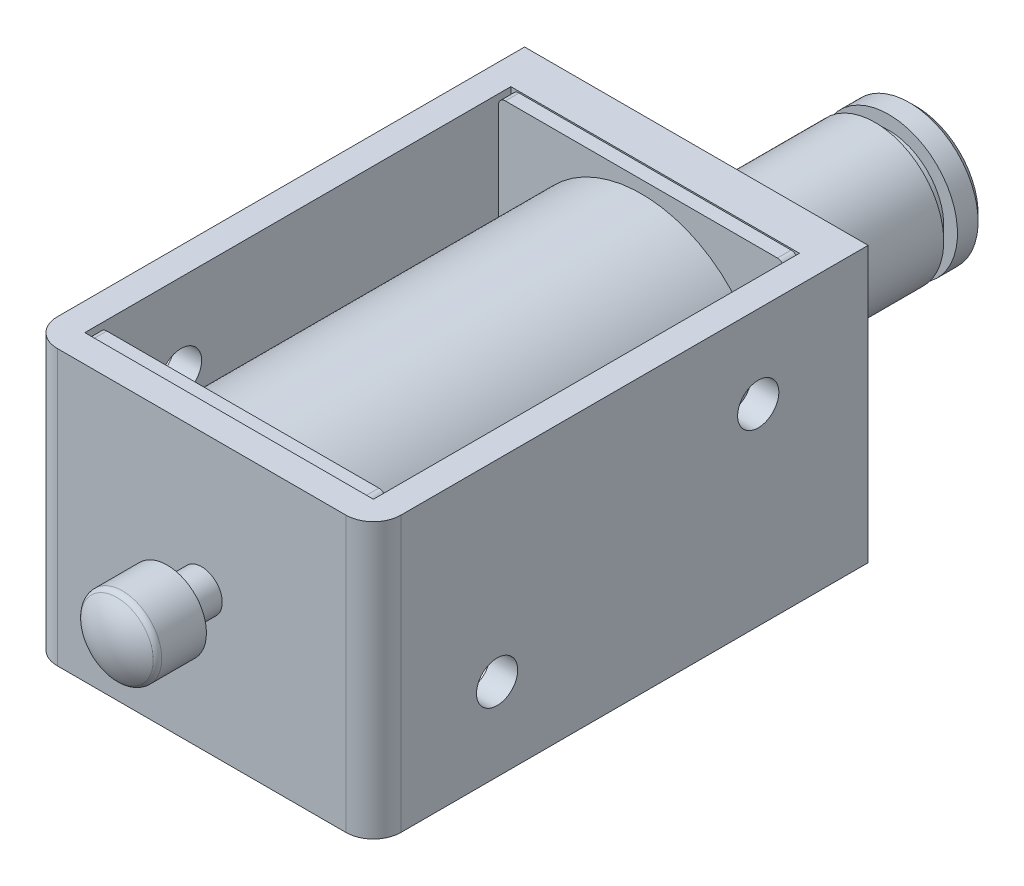
SolidWorks part; units mm, degrees
ref_plane "正面" through (0, 0, 0) normal (0, 0, 1) x (1, 0, 0)
ref_plane "平面" through (0, 0, 0) normal (0, 1, 0) x (1, 0, 0)
ref_plane "右側面" through (0, 0, 0) normal (1, 0, 0) x (0, 0, -1)
sketch "ｽｹｯﾁ1" plane through (0, 0, 0) normal (0, 1, 0) x (1, 0, 0)
  line L0 (2, 17.5) -> (0, 17.5) construction
  line L1 (2, 0) -> (23, 0)
  line L2 (0, 2) -> (0, 36)
  line L3 (0, 36) -> (25, 36)
  line L4 (25, 2) -> (25, 36)
  line L5 (2, 33) -> (23, 33)
  line L6 (2, 33) -> (2, 2)
  line L7 (2, 2) -> (23, 2)
  line L8 (23, 33) -> (23, 2)
  line L9 (23, 17.5) -> (25, 17.5) construction
  line L10 (12.5, 2) -> (12.5, 0) construction
  line L11 (12.5, 33) -> (12.5, 36) construction
  arc A0 (2, 0) -> (0, 2) centre (2, 2) cw
  arc A1 (23, 0) -> (25, 2) centre (23, 2) ccw
  point P19 (0, 0)
  point P22 (25, 0)
  dimension "D5" = 2
  dimension "D1" = 25
  dimension "D2" = 36
  dimension "D3" = 2
  dimension "D4" = 3
extrude "ﾎﾞｽ - 押し出し1" add sketch "ｽｹｯﾁ1" along normal blind 20
sketch "ｽｹｯﾁ14" plane through (25, 0, 0) normal (1, 0, 0) x (0, 0, -1)
  line L0 (0, 6) -> (36, 6) construction
  line L1 (0, 20) -> (0, 0) construction
  line L2 (36, 20) -> (36, 0) construction
  line L3 (36, 14) -> (0, 14) construction
  line L4 (9, 0) -> (9, 20) construction
  line L5 (2, 0) -> (36, 0) construction
  line L6 (2, 20) -> (36, 20) construction
  line L7 (28, 20) -> (28, 0) construction
  circle A0 centre (9, 6) radius 1.5
  circle A1 centre (28, 14) radius 1.5
  point P20 (0, 0)
  dimension "D1" = 3
  dimension "D2" = 6
  dimension "D3" = 9
  dimension "D4" = 6
  dimension "D5" = 8
extrude "ｶｯﾄ - 押し出し5" cut sketch "ｽｹｯﾁ14" against normal up to next
sketch "ｽｹｯﾁ15" plane through (0, 0, 0) normal (-1, 0, 0) x (0, 0, 1)
  line L0 (-36, 6) -> (0, 6) construction
  line L1 (-36, 20) -> (-36, 0) construction
  line L2 (0, 20) -> (0, 0) construction
  line L3 (-36, 14) -> (0, 14) construction
  line L4 (-28, 0) -> (-28, 20) construction
  line L5 (-36, 0) -> (-2, 0) construction
  line L6 (-36, 20) -> (-2, 20) construction
  line L7 (-9, 20) -> (-9, 0) construction
  circle A0 centre (-28, 6) radius 1.5
  circle A1 centre (-9, 14) radius 1.5
  dimension "D5" = 3
  dimension "D1" = 8
  dimension "D2" = 6
  dimension "D3" = 9
  dimension "D4" = 6
extrude "ｶｯﾄ - 押し出し6" cut sketch "ｽｹｯﾁ15" against normal up to next
sketch "ｽｹｯﾁ2" plane through (0, 0, -2) normal (0, 0, -1) x (-1, 0, 0)
  line L18 (-22.9, 0.1) -> (-2.1, 0.1)
  line L19 (-2.1, 0.1) -> (-2.1, 19.9)
  line L20 (-22.9, 19.9) -> (-22.9, 0.1)
  line L21 (-2.1, 19.9) -> (-22.9, 19.9)
  line L22 (-22.4, 0.1) -> (-2.6, 0.1)
  line L23 (-2.1, 0.6) -> (-2.1, 19.4)
  line L24 (-22.9, 19.4) -> (-22.9, 0.6)
  line L25 (-2.6, 19.9) -> (-22.4, 19.9)
  arc A4 (-22.4, 0.1) -> (-22.9, 0.6) centre (-22.4, 0.6) cw
  arc A5 (-2.6, 0.1) -> (-2.1, 0.6) centre (-2.6, 0.6) ccw
  arc A6 (-2.1, 19.4) -> (-2.6, 19.9) centre (-2.6, 19.4) ccw
  arc A7 (-22.9, 19.4) -> (-22.4, 19.9) centre (-22.4, 19.4) cw
  dimension "D1" = 0.1
  dimension "D2" = 0.5
extrude "ﾎﾞｽ - 押し出し2" add sketch "ｽｹｯﾁ2" along normal blind 1
sketch "ｽｹｯﾁ3" plane through (0, 0, -33) normal (0, 0, 1) x (1, 0, 0)
  line L8 (2.1, 0.1) -> (22.9, 0.1)
  line L9 (22.9, 0.1) -> (22.9, 19.9)
  line L10 (22.9, 19.9) -> (2.1, 19.9)
  line L11 (2.1, 19.9) -> (2.1, 0.1)
  line L12 (2.6, 0.1) -> (22.4, 0.1)
  line L13 (22.9, 0.6) -> (22.9, 19.4)
  line L14 (22.4, 19.9) -> (2.6, 19.9)
  line L15 (2.1, 19.4) -> (2.1, 0.6)
  arc A0 (2.6, 0.1) -> (2.1, 0.6) centre (2.6, 0.6) cw
  arc A1 (22.4, 0.1) -> (22.9, 0.6) centre (22.4, 0.6) ccw
  arc A2 (22.9, 19.4) -> (22.4, 19.9) centre (22.4, 19.4) ccw
  arc A3 (2.6, 19.9) -> (2.1, 19.4) centre (2.6, 19.4) ccw
  dimension "D2" = 0.5
  dimension "D1" = 0.1
extrude "ﾎﾞｽ - 押し出し3" add sketch "ｽｹｯﾁ3" along normal blind 1
sketch "ｽｹｯﾁ4" plane through (0, 0, 0) normal (0, 0, 1) x (1, 0, 0)
  line L0 (12.5, 20) -> (12.5, 0) construction
  line L1 (2, 20) -> (23, 20) construction
  line L2 (2, 0) -> (23, 0) construction
  line L3 (0, 10) -> (25, 10) construction
  line L4 (0, 20) -> (0, 0) construction
  line L5 (25, 20) -> (25, 0) construction
  circle A0 centre (12.5, 10) radius 1.5
  dimension "D1" = 3
extrude "ｶｯﾄ - 押し出し1" cut sketch "ｽｹｯﾁ4" against normal up to surface (3 mm away) up to face at (12.5, 10, -3)
sketch "ｽｹｯﾁ5" plane through (0, 0, -36) normal (0, 0, -1) x (-1, 0, 0)
  line L0 (-12.5, 20) -> (-12.5, 0) construction
  line L1 (-25, 20) -> (0, 20) construction
  line L2 (-25, 0) -> (0, 0) construction
  line L3 (-25, 10) -> (0, 10) construction
  line L4 (-25, 20) -> (-25, 0) construction
  line L5 (0, 20) -> (0, 0) construction
  circle A0 centre (-12.5, 10) radius 5
  dimension "D1" = 10
extrude "ｶｯﾄ - 押し出し2" cut sketch "ｽｹｯﾁ5" against normal up to surface (4 mm away) up to face at (12.5, 10, -32)
ref_plane "平面1" through (0, 10, 0) normal (0, 1, 0) x (1, 0, 0)
sketch "ｽｹｯﾁ6" plane through (0, 10, 0) normal (0, 1, 0) x (1, 0, 0)
  line L0 (12.5, 32) -> (12.5, 3)
  line L1 (22.4, 32) -> (2.6, 32) construction
  line L2 (2.6, 3) -> (22.4, 3) construction
  line L3 (12.5, 3) -> (3.5, 3)
  line L4 (3.5, 3) -> (3.5, 32)
  line L5 (3.5, 32) -> (12.5, 32)
  line L6 (2, 33) -> (2, 2) construction
  dimension "D1" = 1.5
revolve "回転1" add sketch "ｽｹｯﾁ6" angle 360 about L0
sketch "ｽｹｯﾁ7" plane through (0, 0, -3) normal (0, 0, -1) x (-1, 0, 0)
  circle A0 centre (-12.5, 10) radius 1.5
extrude "ﾎﾞｽ - 押し出し4" add sketch "ｽｹｯﾁ7" against normal blind 8
sketch "ｽｹｯﾁ8" plane through (0, 0, -32) normal (0, 0, -1) x (-1, 0, 0)
  circle A0 centre (-12.5, 10) radius 5
extrude "ﾎﾞｽ - 押し出し5" add sketch "ｽｹｯﾁ8" along normal blind 20
sketch "ｽｹｯﾁ10" plane through (0, 0, -52) normal (0, 0, -1) x (-1, 0, 0)
  circle A0 centre (-12.5, 10) radius 1.75
  dimension "D1" = 3.5
extrude "ｶｯﾄ - 押し出し4" cut sketch "ｽｹｯﾁ10" against normal up to surface (20 mm away) up to face at (3.5, 10, -32)
ref_plane "平面2" through (0, 0, -50) normal (0, 0, -1) x (-1, 0, 0)
sketch "ｽｹｯﾁ9" plane through (0, 0, -50) normal (0, 0, -1) x (-1, 0, 0)
  circle A0 centre (-12.5, 10) radius 5
  circle A1 centre (-12.5, 10) radius 4
  dimension "D1" = 8
  dimension "D2" = 10
extrude "ｶｯﾄ - 押し出し3" cut sketch "ｽｹｯﾁ9" against normal blind 1
ref_plane "平面3" through (0, 0, 6) normal (0, 0, 1) x (1, 0, 0)
sketch "ｽｹｯﾁ11" plane through (0, 0, 6) normal (0, 0, 1) x (1, 0, 0)
  circle A0 centre (12.5, 10) radius 2.85
  dimension "D1" = 5.7
extrude "ﾎﾞｽ - 押し出し6" add sketch "ｽｹｯﾁ11" against normal blind 3.5
ref_plane "平面4" through (12.5, 0, 0) normal (-1, 0, 0) x (0, 0, 1)
sketch "ｽｹｯﾁ12" plane through (12.5, 0, 0) normal (-1, 0, 0) x (0, 0, 1)
  line L0 (6, 10) -> (7, 10)
  line L1 (6, 7.15) -> (6, 12.85) construction
  line L3 (6, 12.85) -> (6, 10)
  line L4 (6, 10) -> (2.4387, 10) construction
  arc A0 (7, 10) -> (6, 12.85) centre (2.4387, 10) ccw
  dimension "D1" = 1
revolve "回転2" add sketch "ｽｹｯﾁ12" angle 360 about L0
fillet "ﾌｨﾚｯﾄ1" radius 0.5 1 edges at (15.35, 10, 6)
chamfer "面取り1" distance 0.5 angle 45 1 edges at (7.5, 10, -52)
